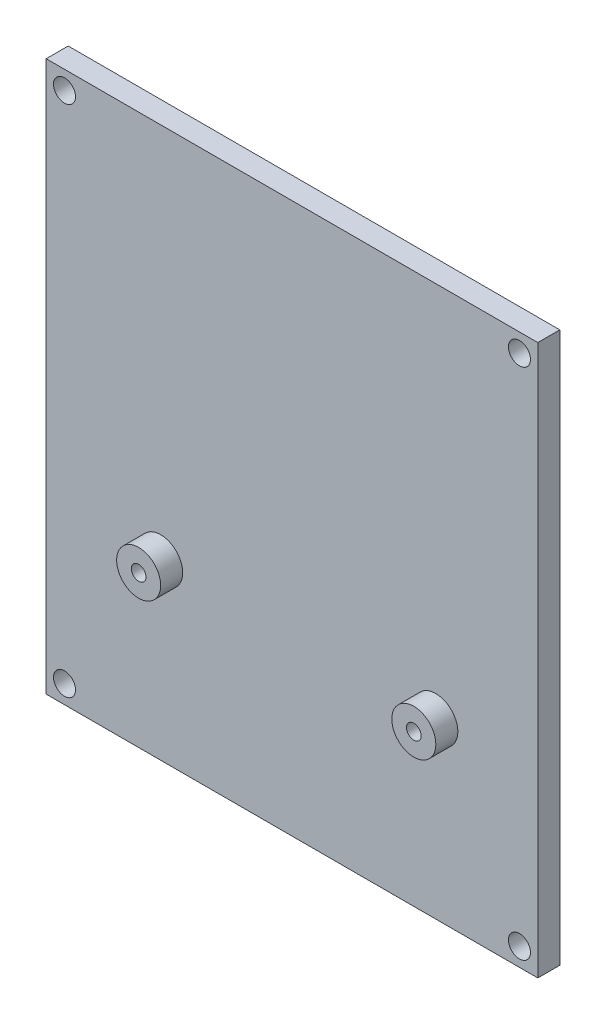
SolidWorks part; units mm, degrees
ref_plane "Front Plane" through (0, 0, 0) normal (0, 0, 1) x (1, 0, 0)
ref_plane "Top Plane" through (0, 0, 0) normal (0, 1, 0) x (1, 0, 0)
ref_plane "Right Plane" through (0, 0, 0) normal (1, 0, 0) x (0, 0, -1)
sketch "Sketch1" plane through (0, 0, 0) normal (0, 0, 1) x (1, 0, 0)
  line L1 (-33.5, -37.5) -> (33.5, -37.5)
  line L2 (-33.5, -37.5) -> (-33.5, 37.5)
  line L3 (-33.5, 37.5) -> (33.5, 37.5)
  line L4 (33.5, -37.5) -> (33.5, 37.5)
  line L5 (-33.5, -37.5) -> (33.5, 37.5) construction
  line L6 (-33.5, 37.5) -> (33.5, -37.5) construction
  point P0 (0, 0)
  dimension "D1" = 67
  dimension "D2" = 75
extrude "Boss-Extrude1" add sketch "Sketch1" along normal blind 3
sketch "Sketch2" plane through (0, 0, 3) normal (0, 0, 1) x (1, 0, 0)
  line L1 (-31, -35) -> (31, -35) construction
  line L2 (-31, -35) -> (-31, 35) construction
  line L3 (-31, 35) -> (31, 35) construction
  line L4 (31, -35) -> (31, 35) construction
  line L5 (-31, -35) -> (31, 35) construction
  line L6 (-31, 35) -> (31, -35) construction
  circle A0 centre (-31, 35) radius 1.5
  circle A1 centre (31, 35) radius 1.5
  circle A2 centre (31, -35) radius 1.5
  circle A3 centre (-31, -35) radius 1.5
  point P0 (0, 0)
  dimension "D3" = 3
  dimension "D1" = 62
  dimension "D2" = 70
extrude "Cut-Extrude1" cut sketch "Sketch2" against normal blind 3
sketch "Sketch3" plane through (0, 0, 3) normal (0, 0, 1) x (1, 0, 0)
  circle A0 centre (-17.8995, -13.8761) radius 1
  circle A1 centre (19.6005, -13.8761) radius 1
  circle A2 centre (-17.8995, -13.8761) radius 3
  circle A3 centre (19.6005, -13.8761) radius 3
  dimension "D1" = 2
  dimension "D3" = 6
  dimension "D2" = 37.5
extrude "Boss-Extrude2" add sketch "Sketch3" along normal blind 3
